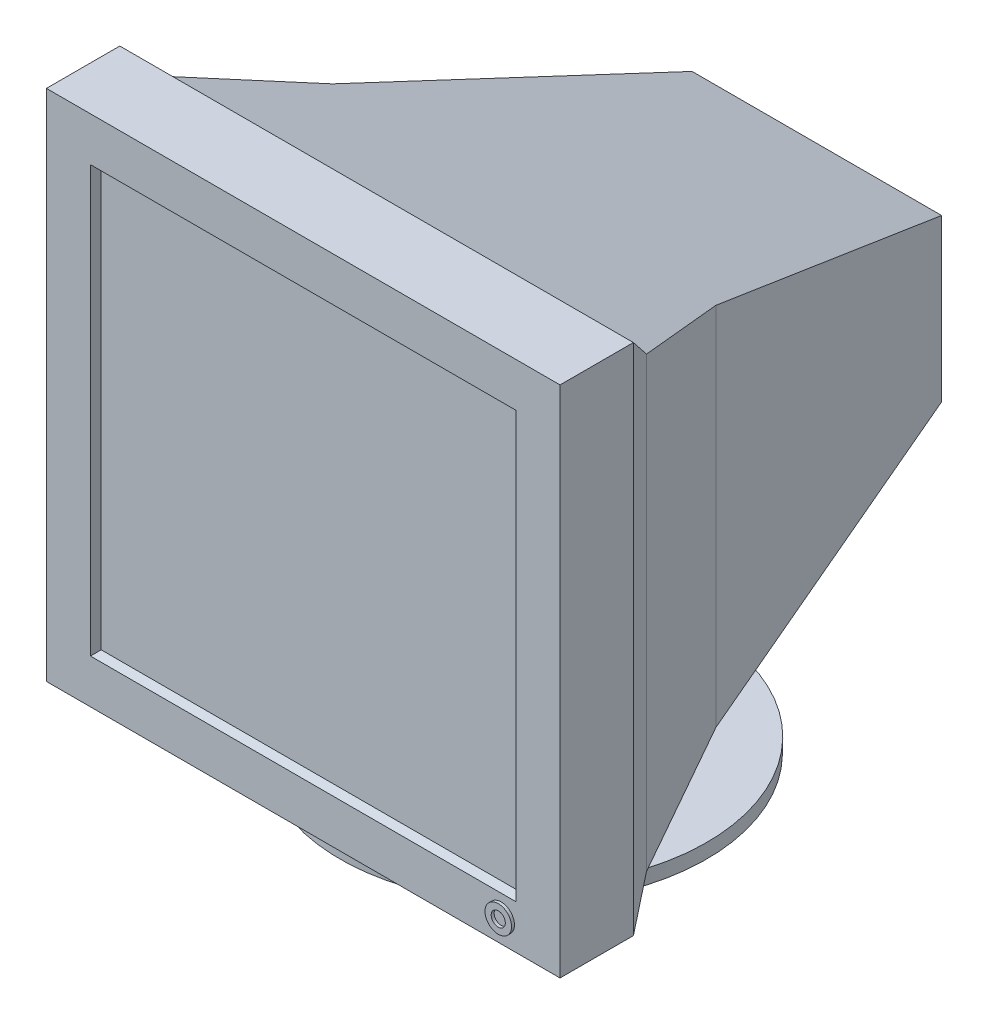
SolidWorks part; units mm, degrees
ref_plane "Alzado" through (0, 0, 0) normal (0, 0, 1) x (1, 0, 0)
ref_plane "Planta" through (0, 0, 0) normal (0, 1, 0) x (1, 0, 0)
ref_plane "Vista lateral" through (0, 0, 0) normal (1, 0, 0) x (0, 0, -1)
sketch "Croquis1" plane through (0, 0, 0) normal (0, 0, 1) x (1, 0, 0)
  line L0 (175, 175) -> (-175, -175) construction
  line L1 (-175, 175) -> (175, 175)
  line L2 (-175, 175) -> (-175, -175)
  line L3 (-175, -175) -> (175, -175)
  line L4 (175, 175) -> (175, -175)
  dimension "D1" = 350
  dimension "D2" = 350
extrude "Saliente-Extruir1" add sketch "Croquis1" against normal blind 350
sketch "Croquis2" plane through (0, 0, 0) normal (0, 0, 1) x (1, 0, 0)
  line L0 (145, 145) -> (-145, -145) construction
  line L1 (-145, 145) -> (145, 145)
  line L2 (-145, 145) -> (-145, -145)
  line L3 (-145, -145) -> (145, -145)
  line L4 (145, 145) -> (145, -145)
  line L5 (175, 175) -> (-175, 175) construction
  line L6 (175, -175) -> (175, 175) construction
  dimension "D1" = 30
  dimension "D2" = 30
extrude "Cortar-Extruir1" cut sketch "Croquis2" against normal blind 5 draft 25
sketch "Croquis3" plane through (175, 0, 0) normal (1, 0, 0) x (0, 0, -1)
  line L0 (50, 175) -> (70, 152.6393)
  line L1 (350, 175) -> (0, 175) construction
  line L2 (70, 152.6393) -> (350, 55)
  line L3 (350, -175) -> (350, 175) construction
  line L4 (350, 55) -> (350, 175)
  line L5 (350, 175) -> (50, 175)
  line L6 (0, -175) -> (0, 175) construction
  line L7 (350, 0) -> (196.4048, 0) construction
  line L8 (350, -175) -> (50, -175)
  line L9 (350, -55) -> (350, -175)
  line L10 (70, -152.6393) -> (350, -55)
  line L11 (50, -175) -> (70, -152.6393)
  dimension "D1" = 30
  dimension "D2" = 50
  dimension "D3" = 70
  dimension "D4" = 120
extrude "Cortar-Extruir2" cut sketch "Croquis3" against normal up to next
sketch "Croquis4" plane through (0, 175, 0) normal (0, 1, 0) x (1, 0, 0)
  line L0 (-85, 350) -> (-175, 350)
  line L1 (-175, 350) -> (175, 350) construction
  line L2 (-175, 350) -> (-175, 50)
  line L3 (-175, 50) -> (-163.916, 70)
  line L4 (-175, 70) -> (175, 70) construction
  line L5 (-163.916, 70) -> (-130.6822, 150.4971)
  line L6 (-130.6822, 150.4971) -> (-85, 350)
  line L7 (0, 350) -> (0, 223.1609) construction
  line L8 (130.6822, 150.4971) -> (85, 350)
  line L9 (163.916, 70) -> (130.6822, 150.4971)
  line L10 (175, 50) -> (163.916, 70)
  line L11 (175, 350) -> (175, 50)
  line L12 (85, 350) -> (175, 350)
  dimension "D1" = 90
extrude "Cortar-Extruir3" cut sketch "Croquis4" against normal up to next
sketch "Croquis5" plane through (0, -175, 0) normal (0, -1, 0) x (1, 0, 0)
  line L0 (0, 0) -> (0, -350) construction
  line L1 (-85, -350) -> (85, -350) construction
  circle A0 centre (0, -150) radius 53.325
  dimension "D1" = 200
extrude "Saliente-Extruir2" add sketch "Croquis5" against normal blind 85 and the other way blind 20
sketch "Croquis6" plane through (0, -195, 0) normal (0, -1, 0) x (1, 0, 0)
  circle A0 centre (0, -150) radius 125
  dimension "D1" = 250
extrude "Saliente-Extruir3" add sketch "Croquis6" along normal blind 10 draft 1
sketch "Croquis7" plane through (0, 0, 0) normal (0, 0, 1) x (1, 0, 0)
  circle A0 centre (134.9079, -159.1988) radius 9.0521
extrude "Saliente-Extruir4" add sketch "Croquis7" along normal blind 2
sketch "Croquis8" plane through (0, 0, 2) normal (0, 0, 1) x (1, 0, 0)
  circle A0 centre (134.9079, -159.1988) radius 4.818
extrude "Cortar-Extruir4" cut sketch "Croquis8" against normal blind 2
